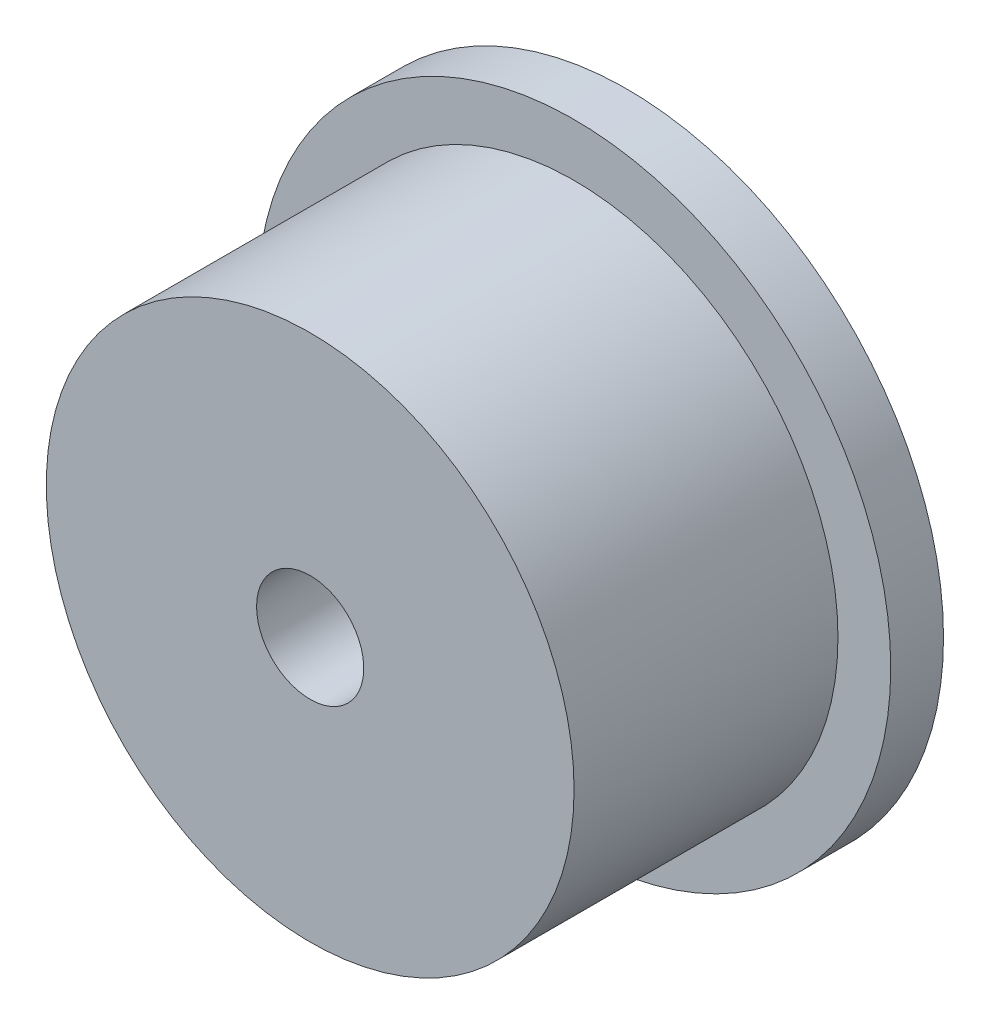
SolidWorks part; units mm, degrees
ref_plane "Front Plane" through (0, 0, 0) normal (0, 0, 1) x (1, 0, 0)
ref_plane "Top Plane" through (0, 0, 0) normal (0, 1, 0) x (1, 0, 0)
ref_plane "Right Plane" through (0, 0, 0) normal (1, 0, 0) x (0, 0, -1)
sketch "Sketch1" plane through (0, 0, 0) normal (0, 1, 0) x (1, 0, 0)
  line L0 (0, 0) -> (0, 101.6) construction
  line L1 (-39.3063, 22.701) -> (52.4393, 22.701) construction
  line L2 (0, 71.1205) -> (0, 86.3605)
  line L3 (0, 86.3605) -> (-15.24, 86.3605)
  line L4 (-15.24, 86.3605) -> (-15.24, 83.8205)
  line L5 (-15.24, 83.8205) -> (-12.7, 83.8205)
  line L6 (-12.7, 83.8205) -> (-12.7, 71.1205)
  line L7 (-12.7, 71.1205) -> (0, 71.1205)
  circle A0 centre (0, 0) radius 15.24 construction
  circle A1 centre (0, 101.6) radius 8.89 construction
  dimension "D2" = 30.48
  dimension "D3" = 17.78
  dimension "D1" = 101.6
  dimension "D4" = 22.701
  dimension "D6" = 12.7
  dimension "D7" = 15.24
  dimension "D8" = 2.54
  dimension "D5" = 0
  dimension "D9" = 12.7
revolve "Revolve1" add sketch "Sketch1" angle 360 about L0
sketch "Sketch2" plane through (0, 0, -86.3605) normal (0, 0, -1) x (-1, 0, 0)
  circle A0 centre (0, 0) radius 2.5797
  dimension "D1" = 5.1594
extrude "Cut-Extrude1" cut sketch "Sketch2" against normal through all
sketch "Sketch3" plane through (0, 0, -86.3605) normal (0, 0, -1) x (-1, 0, 0)
  circle A0 centre (0, 0) radius 4.7625
  dimension "D1" = 9.525
extrude "Cut-Extrude2" cut sketch "Sketch3" against normal blind 1.4732
equation "\"D3@Sketch1\"=\"DiffLinkID\"+2*(\"DiffLinkTHK\")"
equation "\"DiffLinkID\"= .5in"
equation "\"DiffLinkTHK\"= .1in"
equation "\"SupportLinkID\"= 1in"
equation "\"D2@Sketch1\"=\"SupportLinkID\"+2*(\"DiffLinkTHK\")"
equation "\"D4@Sketch1\"=.8150+2mm"
equation "\"D6@Sketch1\"=\"SupportLinkID\"/2"
equation "\"D7@Sketch1\"=\"SupportLinkID\"/2+(\"DiffLinkTHK\")"
equation "\"D1@Sketch2\"=13/64in"
equation "\"D1@Sketch3\"=3/8"
